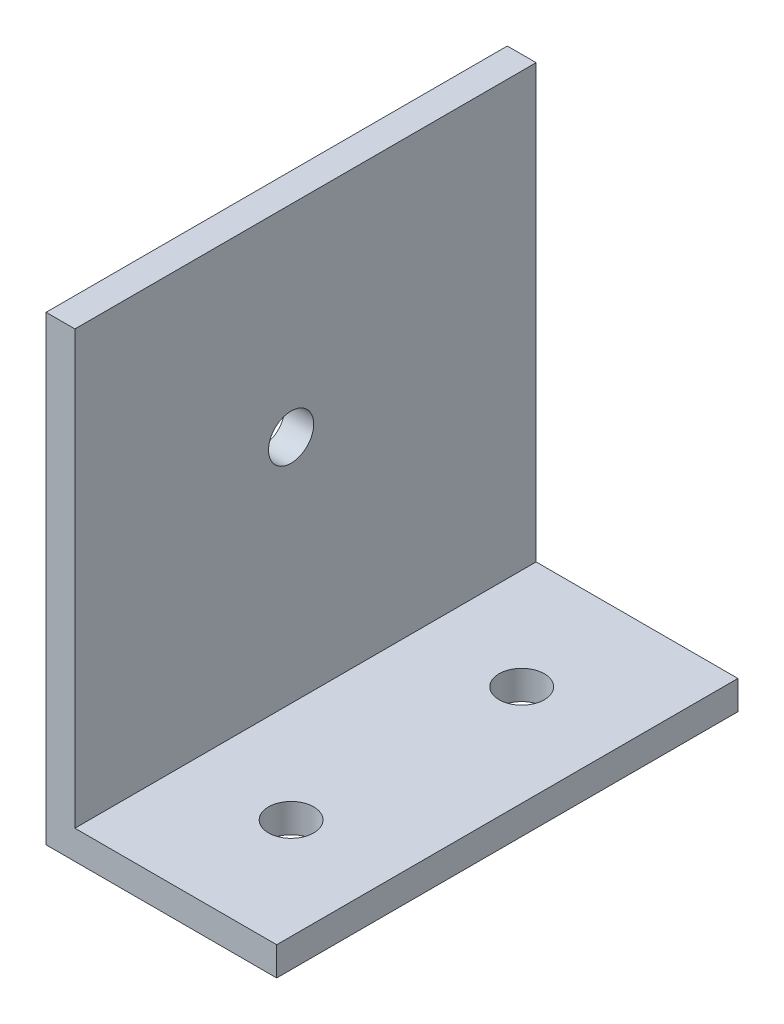
SolidWorks part; units mm, degrees
ref_plane "Front Plane" through (0, 0, 0) normal (0, 0, 1) x (1, 0, 0)
ref_plane "Top Plane" through (0, 0, 0) normal (0, 1, 0) x (1, 0, 0)
ref_plane "Right Plane" through (0, 0, 0) normal (1, 0, 0) x (0, 0, -1)
sketch "Sketch1" plane through (0, 0, 0) normal (0, 0, 1) x (1, 0, 0)
  line L0 (0, 0) -> (0, 50.8)
  line L1 (0, 50.8) -> (3.175, 50.8)
  line L2 (3.175, 50.8) -> (3.175, 3.175)
  line L3 (3.175, 3.175) -> (25.4, 3.175)
  line L4 (25.4, 3.175) -> (25.4, 0)
  line L5 (25.4, 0) -> (0, 0)
  dimension "D1" = 50.8
  dimension "D2" = 25.4
  dimension "D3" = 3.175
  dimension "D4" = 3.175
extrude "Boss-Extrude1" add sketch "Sketch1" along normal blind 50.8
sketch "Sketch2" plane through (0, 0, 0) normal (1, 0, 0) x (0, 0, -1)
  line L1 (-50.8, 3.175) -> (-50.8, 50.8) construction
  line L2 (-50.8, 3.175) -> (0, 3.175) construction
  circle A0 centre (-26.9875, 28.575) radius 2.4892
  dimension "D1" = 4.9784
  dimension "D2" = 23.8125
  dimension "D3" = 25.4
extrude "Cut-Extrude1" cut sketch "Sketch2" along normal through all
sketch "Sketch3" plane through (0, 0, 0) normal (0, 1, 0) x (1, 0, 0)
  line L0 (25.4, -50.8) -> (3.175, -50.8) construction
  circle A0 centre (14.2875, -38.1) radius 2.4892
  circle A1 centre (14.2875, -12.7) radius 2.4892
  point P6 (14.2875, -50.8)
  dimension "D1" = 4.9784
  dimension "D2" = 12.7
  dimension "D3" = 25.4
extrude "Cut-Extrude2" cut sketch "Sketch3" along normal through all
